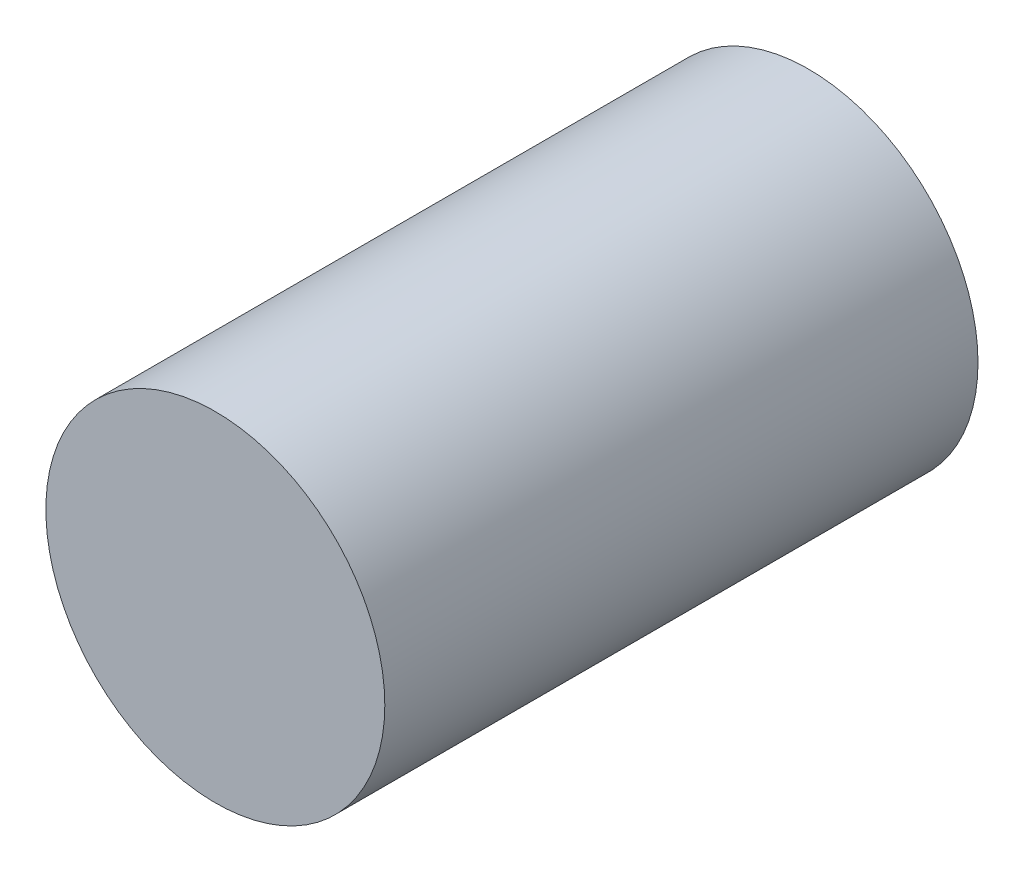
SolidWorks part; units mm, degrees
material "SKD11淬火HRC56-60"
ref_plane "前基準面" through (0, 0, 0) normal (0, 0, 1) x (1, 0, 0)
ref_plane "上基準面" through (0, 0, 0) normal (0, 1, 0) x (1, 0, 0)
ref_plane "右基準面" through (0, 0, 0) normal (1, 0, 0) x (0, 0, -1)
sketch "草图1" plane through (0, 0, 0) normal (0, 0, 1) x (1, 0, 0)
  circle A0 centre (0, 0) radius 10
  dimension "D1" = 20
extrude "凸台-拉伸1" add sketch "草图1" along normal blind 35
sketch "草图3" plane through (0, 0, 0) normal (0, 0, -1) x (-1, 0, 0)
  circle A0 centre (0, 0) radius 9.5
  circle A2 centre (0, 0) radius 10 construction
  dimension "D1" = 0.5
extrude "切除-拉伸1" cut sketch "草图3" against normal blind 20
